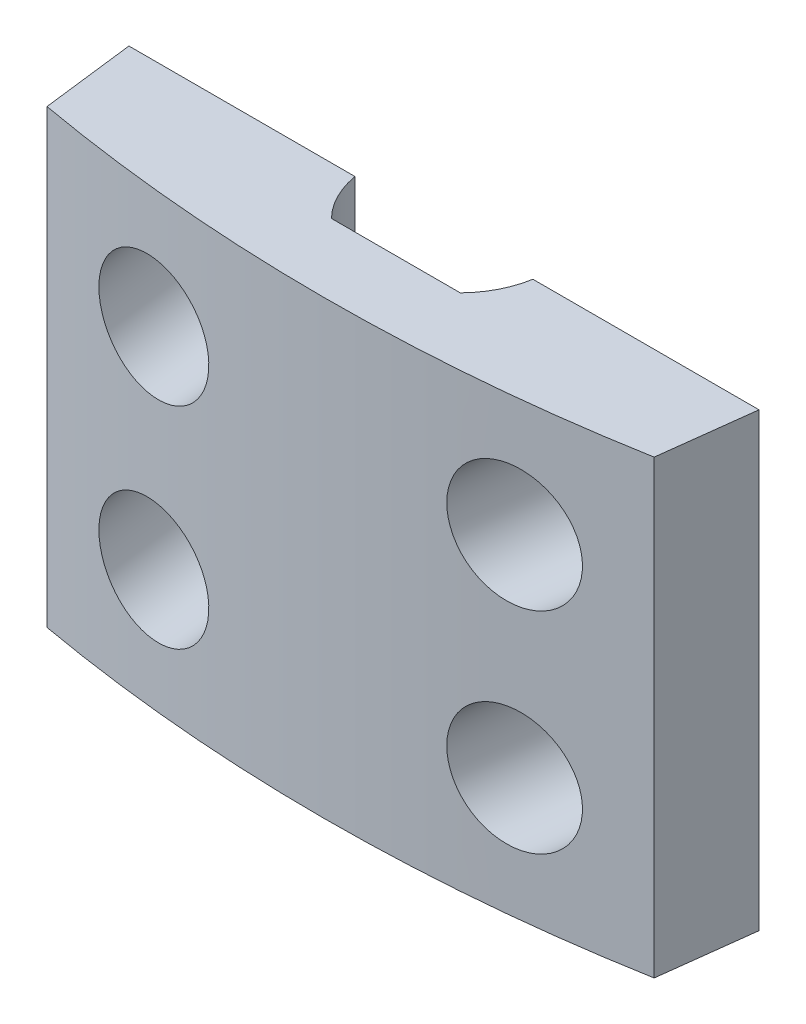
SolidWorks part; units mm, degrees
material "1023 碳钢板 (SS)"
ref_plane "前视基准面" through (0, 0, 0) normal (0, 0, 1) x (1, 0, 0)
ref_plane "上视基准面" through (0, 0, 0) normal (0, 1, 0) x (1, 0, 0)
ref_plane "右视基准面" through (0, 0, 0) normal (1, 0, 0) x (0, 0, -1)
sketch "草图1" plane through (0, 0, 0) normal (0, 1, 0) x (1, 0, 0)
  line L0 (0, 57.5) -> (0, 53) construction
  line L1 (0, 0) -> (7.617, 62.0354) construction
  line L2 (-2.1424, 50.9) -> (2.1424, 50.9)
  line L3 (0, 53) -> (0, 48.5) construction
  line L4 (-12, 48.5) -> (12, 48.5) construction
  line L5 (-10.0947, 49.3931) -> (-10.4761, 52.4993)
  line L6 (-10.4761, 52.4993) -> (-2.9579, 52.4993)
  line L7 (10.4761, 52.4993) -> (2.9579, 52.4993)
  line L8 (10.0947, 49.3931) -> (10.4761, 52.4993)
  line L9 (0, 0) -> (-7.5627, 61.5932) construction
  line L10 (-8.4611, 52.4993) -> (-8.0394, 49.0648) construction
  line L11 (-4.4926, 53) -> (-3.9568, 48.6363) construction
  line L12 (4.4926, 53) -> (3.9568, 48.6363) construction
  line L13 (8.4611, 52.4993) -> (8.0394, 49.0648) construction
  line L14 (-13.037, 53) -> (13.037, 53) construction
  arc A0 (2.1424, 50.9) -> (2.9579, 52.4993) centre (0, 53) ccw
  arc A1 (-2.9579, 52.4993) -> (-2.1424, 50.9) centre (0, 53) ccw
  circle A2 centre (0, 106) radius 57.5 construction
  arc A3 (10.0947, 49.3931) -> (-10.0947, 49.3931) centre (0, 106) cw
  point P14 (0, 48.5)
  point P27 (6.5076, 53)
  point P30 (0, 53)
  dimension "D3" = 6
  dimension "D7" = 115
  dimension "D10" = 0.5007
  dimension "D2" = 4.5
  dimension "D4" = 4
  dimension "D5" = 4.5
  dimension "D6" = 24
  dimension "D8" = 2
  dimension "D9" = 4
  dimension "D11" = 2
  dimension "D12" = 2
  dimension "D13" = 2.1
  dimension "D14" = 106
  dimension "D15" = 12.9182
  dimension "D16" = 97
  dimension "D17" = 2
  dimension "D18" = 97
extrude "凸台-拉伸1" add sketch "草图1" along normal blind 15
sketch3d "3D草图2" plane through (0, 0, 0) normal (0, 0, 1) x (1, 0, 0)
  dimension "D1" = 263
sketch3d "3D草图6" plane through (0, 0, 0) normal (0, 0, 1) x (1, 0, 0)
  dimension "D1" = 270
sketch3d "3D草图7" plane through (0, 0, 0) normal (0, 0, 1) x (1, 0, 0)
  dimension "D1" = 12.918
sketch3d "3D草图8" plane through (0, 0, 0) normal (0, 0, 1) x (1, 0, 0)
  dimension "D1" = 90
sketch "草图2" plane through (-12.8219, 0, -104.4257) normal (0.1219, 0, 0.9925) x (0.9925, 0, -0.1219)
  line L0 (16.039, 15) -> (-4, 15) construction
  line L1 (-4, 0) -> (16.039, 0) construction
  line L2 (0.0002, 50) -> (0.0002, -50) construction
  circle A0 centre (0.0002, 4) radius 2
  circle A1 centre (0.0002, 11) radius 2
  dimension "D1" = 4
  dimension "D2" = 4
  dimension "D3" = 4
  dimension "D4" = 4
extrude "切除-拉伸1" cut sketch "草图2" along normal blind 62
sketch3d "3D草图9" plane through (0, 0, 0) normal (0, 0, 1) x (1, 0, 0)
  dimension "D1" = 97
sketch3d "3D草图10" plane through (0, 0, 0) normal (0, 0, 1) x (1, 0, 0)
  dimension "D1" = 12.918
sketch3d "3D草图11" plane through (0, 0, 0) normal (0, 0, 1) x (1, 0, 0)
  dimension "D1" = 90
sketch "草图4" plane through (12.8219, 0, -104.4257) normal (0.1219, 0, -0.9925) x (-0.9925, 0, -0.1219)
  line L0 (-4, 15) -> (3.4622, 15) construction
  line L1 (-4, 0) -> (3.4622, 0) construction
  line L2 (0.0002, 50) -> (0.0002, -50) construction
  circle A0 centre (0.0002, 11) radius 2
  circle A1 centre (0.0002, 4) radius 2
  dimension "D1" = 4
  dimension "D2" = 4
  dimension "D3" = 4
  dimension "D4" = 4
extrude "切除-拉伸2" cut sketch "草图4" against normal blind 62
